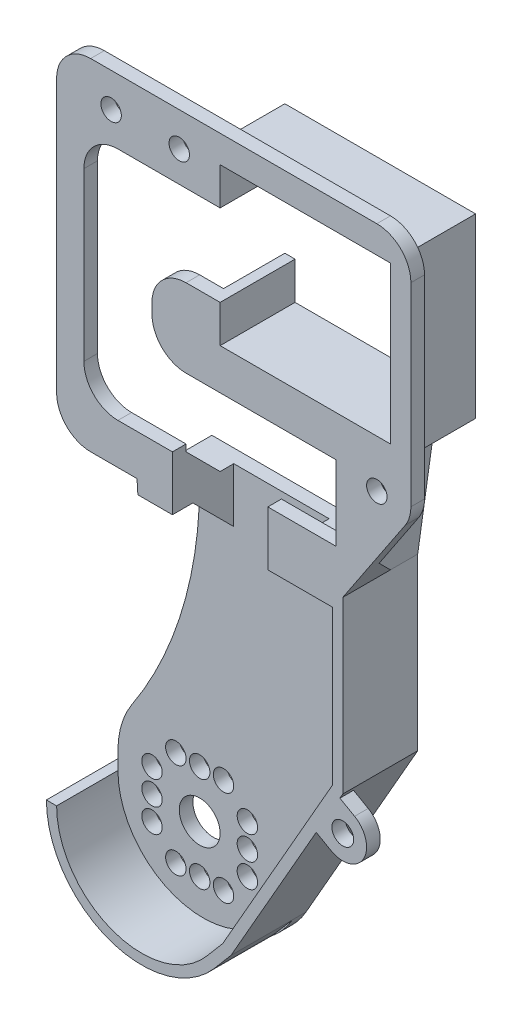
SolidWorks part; units mm, degrees
ref_plane "前视基准面" through (0, 0, 0) normal (0, 0, 1) x (1, 0, 0)
ref_plane "上视基准面" through (0, 0, 0) normal (0, 1, 0) x (1, 0, 0)
ref_plane "右视基准面" through (0, 0, 0) normal (1, 0, 0) x (0, 0, -1)
sketch "草图1" plane through (0, 0, 0) normal (1, 0, 0) x (0, 0, -1)
  line L0 (0, 0) -> (0, 58)
  line L1 (0, 58) -> (-9, 58)
  line L2 (-9, 58) -> (-9, 110)
  line L3 (-7, 110) -> (-7, 60)
  line L4 (-7, 60) -> (2, 60)
  line L5 (2, 60) -> (2, 0)
  line L6 (2, 0) -> (0, 0)
  line L7 (-7, 110) -> (-9, 110)
  point P9 (-2.5, 60)
  dimension "D1" = 2
  dimension "D2" = 2
  dimension "D3" = 2
  dimension "D4" = 9
  dimension "D5" = 52
  dimension "D6" = 60
extrude "凸台-拉伸1" add sketch "草图1" along normal blind 52
sketch "草图2" plane through (0, 0, 7) normal (0, 0, -1) x (-1, 0, 0)
  line L0 (-49, 106) -> (-49, 83)
  line L1 (-49, 83) -> (-24, 83)
  line L2 (-24, 83) -> (-24, 88.5)
  line L3 (-24, 88.5) -> (-14, 88.5)
  line L4 (-14, 88.5) -> (-14, 77)
  line L5 (-14, 77) -> (-41, 77)
  line L6 (-41, 77) -> (-41, 66)
  line L7 (-41, 66) -> (-31, 66)
  line L8 (-31, 66) -> (-31, 58)
  line L10 (-31, 58) -> (-17, 58)
  line L11 (-17, 58) -> (-17, 66)
  line L12 (-17, 66) -> (-4, 66)
  line L13 (-4, 66) -> (-4, 100.5)
  line L14 (-4, 100.5) -> (-24, 100.5)
  line L15 (-24, 100.5) -> (-24, 106)
  line L16 (-24, 106) -> (-49, 106)
  line L17 (-49, 94.5) -> (31.6365, 94.5) construction
  line L20 (-52, 60) -> (-52, 110) construction
  line L21 (-52, 58) -> (0, 58) construction
  point P20 (-14, 100.5)
  point P21 (-24, 85.75)
  dimension "D1" = 23
  dimension "D2" = 25
  dimension "D3" = 12
  dimension "D4" = 6
  dimension "D5" = 20
  dimension "D6" = 10
  dimension "D7" = 17
  dimension "D8" = 6
  dimension "D9" = 8
  dimension "D10" = 18
  dimension "D11" = 14
  dimension "D12" = 3
  dimension "D13" = 25
extrude "切除-拉伸1" cut sketch "草图2" against normal up to next and the other way blind 7
sketch "草图3" plane through (0, 0, -2) normal (0, 0, -1) x (-1, 0, 0)
  line L0 (-42, 35) -> (-22, 0)
  line L1 (-52, 60) -> (-52, 110) construction
  line L2 (-52, 0) -> (0, 0) construction
  line L3 (-22, 0) -> (-52, 0)
  line L4 (-52, 0) -> (-52, 75)
  line L5 (0, 0) -> (0, 60) construction
  line L6 (-15.5, 19) -> (-3.1235, 19) construction
  line L7 (-24.971, 12) -> (-2.1095, 12) construction
  line L8 (-15.5, 5) -> (-3.1235, 5) construction
  line L9 (-12, 19) -> (-12, -1.1388) construction
  line L10 (-5, 15.5) -> (-5, 8.3211) construction
  line L11 (-19, 15.5) -> (-19, 8.3211) construction
  line L12 (0, 60) -> (-11.7913, 60)
  line L13 (-17, 60) -> (0, 60) construction
  line L14 (0, 60) -> (0, 19)
  line L15 (-42, 60) -> (-42, 35)
  line L17 (-42, 60) -> (-52, 75)
  line L18 (-52, 60) -> (0, 60) construction
  line L19 (-52, 60) -> (-31, 60) construction
  line L20 (0, 60) -> (0, 110) construction
  line L21 (-52, 110) -> (0, 110) construction
  circle A0 centre (-15.5, 19) radius 1.5
  circle A1 centre (-12, 19) radius 1.5
  circle A2 centre (-8.5, 19) radius 1.5
  circle A3 centre (-8.5, 5) radius 1.5
  circle A4 centre (-12, 5) radius 1.5
  circle A5 centre (-15.5, 5) radius 1.5
  circle A6 centre (-5, 15.5) radius 1.5
  circle A7 centre (-5, 12) radius 1.5
  circle A8 centre (-5, 8.5) radius 1.5
  circle A9 centre (-19, 8.5) radius 1.5
  circle A10 centre (-19, 12) radius 1.5
  circle A11 centre (-19, 15.5) radius 1.5
  arc A12 (-11.7913, 60) -> (0, 19) centre (48, 55) ccw
  circle A13 centre (-8, 105) radius 1.5
  circle A14 centre (-47, 76) radius 1.5
  circle A15 centre (-18, 105) radius 1.5
  circle A16 centre (-12, 12) radius 3
  dimension "D4" = 3
  dimension "D5" = 3
  dimension "D6" = 3
  dimension "D8" = 3.5
  dimension "D9" = 3.5
  dimension "D10" = 3
  dimension "D11" = 3
  dimension "D12" = 3
  dimension "D13" = 14
  dimension "D16" = 120
  dimension "D20" = 3
  dimension "D21" = 3
  dimension "D22" = 8
  dimension "D24" = 5
  dimension "D26" = 3
  dimension "D27" = 10
  dimension "D29" = 6
  dimension "D31" = 48
  dimension "D1" = 22
  dimension "D2" = 3.5
  dimension "D3" = 3.5
  dimension "D7" = 14
  dimension "D14" = 12
  dimension "D15" = 12
  dimension "D17" = 55
  dimension "D18" = 25
  dimension "D19" = 15
  dimension "D23" = 5
  dimension "D25" = 16
  dimension "D28" = 5
  dimension "D30" = 10
extrude "切除-拉伸2" cut sketch "草图3" against normal through all
fillet "圆角1" radius 5 8 edges at (4, 66, 8) (4, 100.5, 8) (14, 77, 8) (14, 88.5, 8) (52, 110, 8) (52, 75, 8) (0, 60, 8) (0, 110, 8)
chamfer "倒角1" distance 5 angle 45 2 edges at (14.3957, 60, 7) (36.5, 60, 7)
fillet "圆角2" radius 12.5 3 edges at (22, 0, -1) (0, 0, -1) (0, 19, -1)
sketch "草图4" plane through (0, 0, 7) normal (0, 0, -1) x (-1, 0, 0)
  line L0 (-24, 88.5) -> (-24, 83)
  line L1 (-24, 83) -> (-49, 83)
  line L2 (-49, 83) -> (-49, 106)
  line L3 (-49, 106) -> (-24, 106)
  line L4 (-24, 106) -> (-24, 100.5)
  line L5 (-24, 100.5) -> (-22.5, 100.5)
  line L6 (-9, 100.5) -> (-24, 100.5) construction
  line L7 (-22.5, 100.5) -> (-22.5, 107.5)
  line L8 (-22.5, 107.5) -> (-50.5, 107.5)
  line L9 (-50.5, 107.5) -> (-50.5, 81.5)
  line L10 (-50.5, 81.5) -> (-45, 81.5)
  line L11 (-22.5, 81.5) -> (-22.5, 88.5)
  line L12 (-24, 88.5) -> (-19, 88.5) construction
  line L13 (-22.5, 88.5) -> (-24, 88.5)
  line L14 (-42, 60) -> (-45, 81.5)
  line L15 (-42, 60) -> (-40.4855, 60)
  line L16 (-31, 60) -> (-42, 60) construction
  line L17 (-40.4855, 60) -> (-43.4855, 81.5)
  line L19 (-43.4855, 81.5) -> (-22.5, 81.5)
  dimension "D1" = 1.5
  dimension "D2" = 1.5
  dimension "D3" = 1.5
  dimension "D4" = 1.5
  dimension "D5" = 1.5
  dimension "D6" = 5.5
extrude "凸台-拉伸2" add sketch "草图4" along normal blind 9
sketch "草图6" plane through (0, 0, 0) normal (0, 0, 1) x (1, 0, 0)
  line L0 (42, 58) -> (42, 35)
  line L1 (42, 35) -> (25.599, 6.2983)
  line L2 (24.3701, 7.171) -> (40.5, 35.3983)
  line L3 (40.5, 35.3983) -> (40.5, 58)
  line L4 (42, 58) -> (31, 58) construction
  line L5 (40.5, 58) -> (42, 58)
  line L7 (24.3701, 7.171) -> (22.1721, 4.5816)
  line L8 (25.599, 6.2983) -> (23.1142, 3.371)
  line L9 (0, 12.5) -> (-1.5, 12.5)
  arc A3 (0, 12.5) -> (22.1721, 4.5816) centre (12.5, 12.5) ccw
  arc A4 (-1.5, 12.5) -> (23.1142, 3.371) centre (12.5, 12.5) ccw
  point P4 (23.1142, 3.371)
  dimension "D3" = 25
  dimension "D4" = 28
  dimension "D1" = 1.5
  dimension "D2" = 1.5
extrude "凸台-拉伸3" add sketch "草图6" along normal blind 9 and the other way blind 2
chamfer "倒角3" distance 6 angle 45 2 edges at (14.4625, 58, 0) (35.75, 58, 0)
sketch "草图7" plane through (0, 0, -2) normal (0, 0, -1) x (-1, 0, 0)
  line L0 (-41.5826, 34.2696) -> (-43.7365, 33.0389)
  line L1 (-25.599, 6.2983) -> (-42, 35) construction
  line L2 (-38.1097, 28.1919) -> (-40.2635, 26.9611)
  line L3 (-41.5826, 34.2696) -> (-38.1097, 28.1919)
  arc A0 (-43.7365, 33.0389) -> (-40.2635, 26.9611) centre (-42, 30) ccw
  circle A1 centre (-42, 30) radius 1.6
  dimension "D1" = 3.2
  dimension "D2" = 7
  dimension "D4" = 42
  dimension "D3" = 30
extrude "凸台-拉伸4" add sketch "草图7" along normal blind 2 from offset 11
